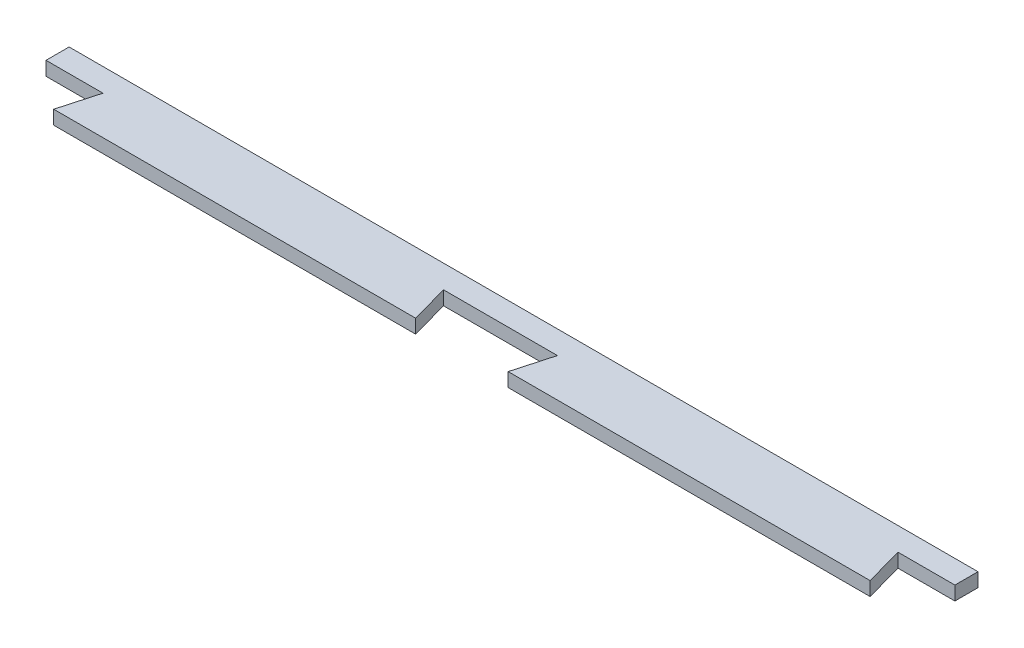
SolidWorks part; units mm, degrees
ref_plane "Front Plane" through (0, 0, 0) normal (0, 0, 1) x (1, 0, 0)
ref_plane "Top Plane" through (0, 0, 0) normal (0, 1, 0) x (1, 0, 0)
ref_plane "Right Plane" through (0, 0, 0) normal (1, 0, 0) x (0, 0, -1)
sketch "Sketch1" plane through (0, 0, 0) normal (0, 1, 0) x (1, 0, 0)
  line L0 (0, 25) -> (37, 25)
  line L1 (0, 0) -> (590, 0)
  line L2 (0, 0) -> (0, 35)
  line L3 (0, 35) -> (590, 35)
  line L4 (590, 0) -> (590, 35)
  line L5 (37, 25) -> (30, 0)
  line L6 (295, 35) -> (295, 0) construction
  line L7 (332, 25) -> (258, 25)
  line L8 (258, 25) -> (265, 0)
  line L9 (332, 25) -> (325, 0)
  line L10 (590, 25) -> (553, 25)
  line L11 (553, 25) -> (560, 0)
  line L13 (0, 35) -> (590, 35)
  line L14 (0, 35) -> (0, 40)
  line L15 (0, 40) -> (590, 40)
  line L16 (590, 35) -> (590, 40)
  point P15 (295, 17.5)
  dimension "D1" = 590
  dimension "D2" = 35
  dimension "D3" = 10
  dimension "D4" = 30
  dimension "D5" = 10
  dimension "D6" = 30
  dimension "D7" = 37
  dimension "D8" = 37
  dimension "D9" = 5
extrude "Boss-Extrude1" add sketch "Sketch1" along normal blind 9
